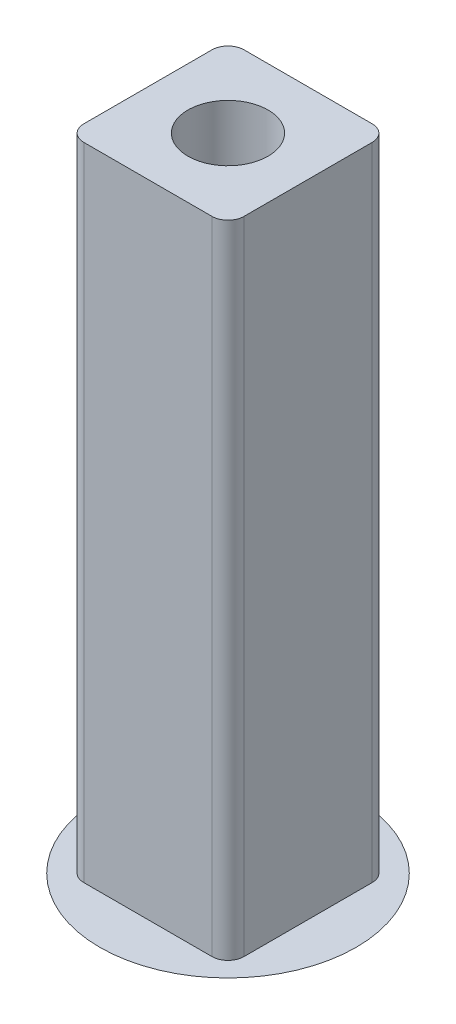
SolidWorks part; units mm, degrees
ref_plane "Спереди" through (0, 0, 0) normal (0, 0, 1) x (1, 0, 0)
ref_plane "Сверху" through (0, 0, 0) normal (0, 1, 0) x (1, 0, 0)
ref_plane "Справа" through (0, 0, 0) normal (1, 0, 0) x (0, 0, -1)
sketch "Эскиз1" plane through (0, 0, 0) normal (0, 1, 0) x (1, 0, 0)
  line L1 (-2, -2.5) -> (2, -2.5)
  line L2 (-2.5, -2) -> (-2.5, 2)
  line L3 (-2, 2.5) -> (2, 2.5)
  line L4 (2.5, -2) -> (2.5, 2)
  line L5 (-2.5, -2.5) -> (2.5, 2.5) construction
  line L6 (-2.5, 2.5) -> (2.5, -2.5) construction
  arc A0 (2, 2.5) -> (2.5, 2) centre (2, 2) cw
  arc A1 (2.5, -2) -> (2, -2.5) centre (2, -2) cw
  arc A2 (-2, -2.5) -> (-2.5, -2) centre (-2, -2) cw
  arc A3 (-2.5, 2) -> (-2, 2.5) centre (-2, 2) cw
  circle A4 centre (0, 0) radius 1.25
  point P0 (0, 0)
  dimension "D3" = 0.5
  dimension "D4" = 2.5
  dimension "D1" = 5
  dimension "D2" = 5
extrude "Бобышка-Вытянуть1" add sketch "Эскиз1" along normal blind 20
sketch "Эскиз2" plane through (0, 0, 0) normal (0, -1, 0) x (1, 0, 0)
  circle A0 centre (0, 0) radius 4
  dimension "D1" = 8
extrude "Бобышка-Вытянуть2" add sketch "Эскиз2" along normal blind 2 draft 64
